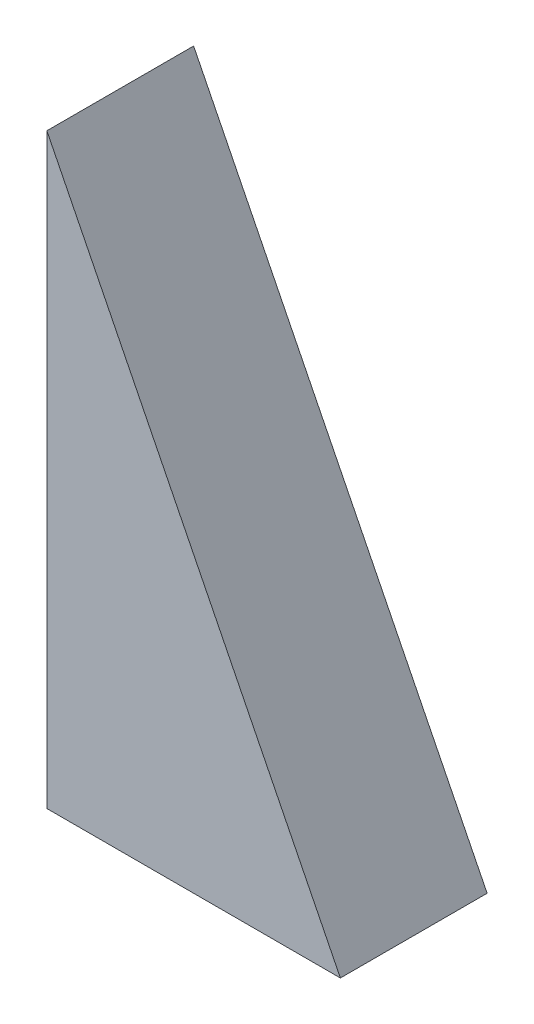
SolidWorks part; units mm, degrees
ref_plane "Front Plane" through (0, 0, 0) normal (0, 0, 1) x (1, 0, 0)
ref_plane "Top Plane" through (0, 0, 0) normal (0, 1, 0) x (1, 0, 0)
ref_plane "Right Plane" through (0, 0, 0) normal (1, 0, 0) x (0, 0, -1)
sketch "Sketch1" plane through (0, 0, 0) normal (0, 0, 1) x (1, 0, 0)
  line L0 (0, 0) -> (0, 40)
  line L1 (0, 40) -> (20, 0)
  line L2 (20, 0) -> (0, 0)
  dimension "D1" = 20
  dimension "D2" = 40
extrude "Boss-Extrude1" add sketch "Sketch1" along normal blind 10
